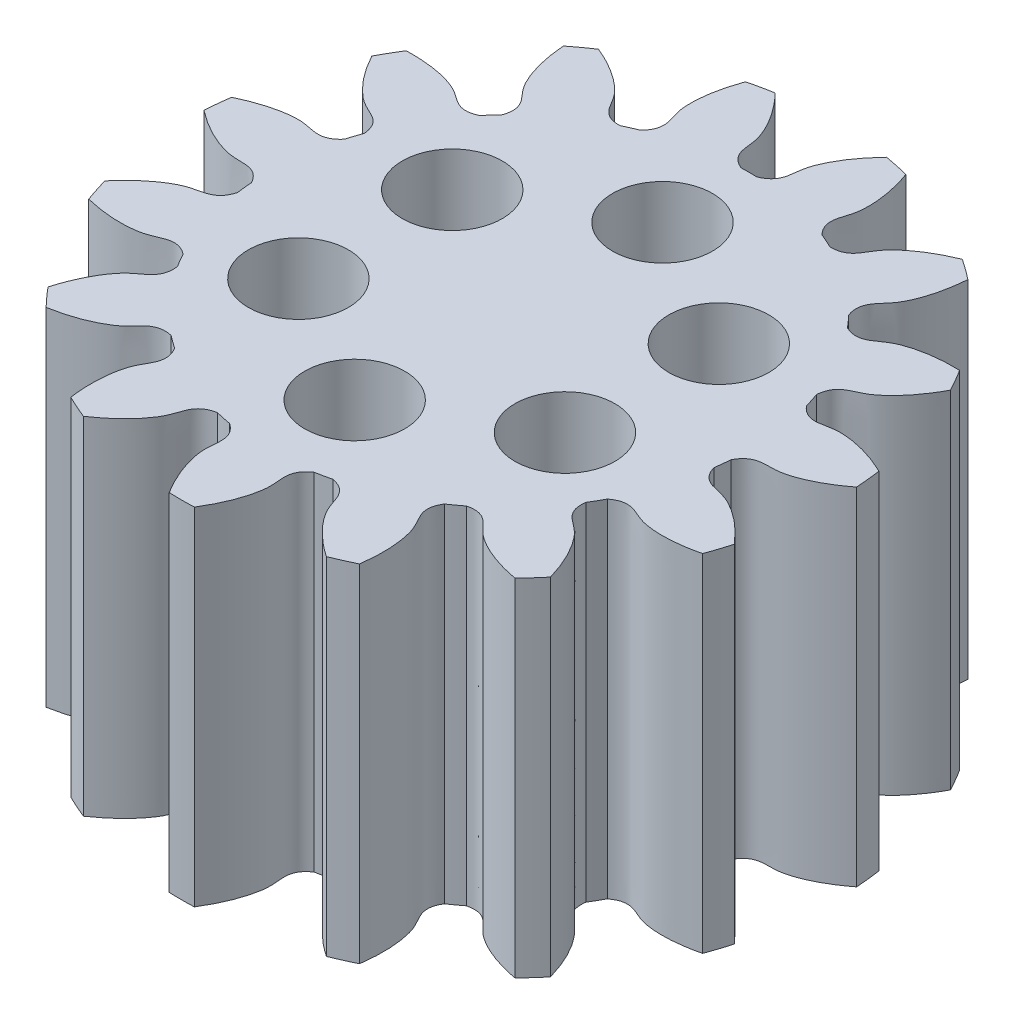
SolidWorks part; units mm, degrees
ref_plane "前视基准面" through (0, 0, 0) normal (0, 0, 1) x (1, 0, 0)
ref_plane "上视基准面" through (0, 0, 0) normal (0, 1, 0) x (1, 0, 0)
ref_plane "右视基准面" through (0, 0, 0) normal (1, 0, 0) x (0, 0, -1)
other "Configuration Table"
sketch "草图1" plane through (0, 0, 0) normal (0, 1, 0) x (1, 0, 0)
  arc A0 (-4.0703, 11.2781) -> (-4.8168, 10.9457) centre (0.638, -0.3013) ccw
  arc A1 (-8.8187, 13.8256) -> (-9.8753, 13.058) centre (0.638, -0.3013) ccw
  arc A2 (-8.373, 8.362) -> (-8.9198, 7.7547) centre (0.638, -0.3013) ccw
  arc A3 (-13.7471, 8.7579) -> (-14.4001, 7.6269) centre (0.638, -0.3013) ccw
  arc A4 (-11.1176, 3.9479) -> (-11.3701, 3.1708) centre (0.638, -0.3013) ccw
  arc A5 (-16.1882, 2.1238) -> (-16.3247, 0.8249) centre (0.638, -0.3013) ccw
  arc A6 (-11.8296, -1.2009) -> (-11.7442, -2.0136) centre (0.638, -0.3013) ccw
  arc A7 (-15.7198, -4.9297) -> (-15.3163, -6.1718) centre (0.638, -0.3013) ccw
  arc A8 (-10.3858, -6.1942) -> (-9.9773, -6.9018) centre (0.638, -0.3013) ccw
  arc A9 (-12.4231, -11.1829) -> (-11.5492, -12.1534) centre (0.638, -0.3013) ccw
  arc A10 (-7.0359, -10.1685) -> (-6.3749, -10.6488) centre (0.638, -0.3013) ccw
  arc A11 (-6.868, -15.5545) -> (-5.6749, -16.0857) centre (0.638, -0.3013) ccw
  arc A12 (-2.3592, -12.4367) -> (-1.5599, -12.6066) centre (0.638, -0.3013) ccw
  arc A13 (-0.015, -17.2888) -> (1.291, -17.2888) centre (0.638, -0.3013) ccw
  arc A14 (2.8358, -12.6066) -> (3.6351, -12.4367) centre (0.638, -0.3013) ccw
  arc A15 (6.9509, -16.0857) -> (8.1439, -15.5545) centre (0.638, -0.3013) ccw
  arc A16 (7.6508, -10.6488) -> (8.3119, -10.1685) centre (0.638, -0.3013) ccw
  arc A17 (12.8252, -12.1534) -> (13.6991, -11.1829) centre (0.638, -0.3013) ccw
  arc A18 (11.2532, -6.9018) -> (11.6618, -6.1942) centre (0.638, -0.3013) ccw
  arc A19 (16.5922, -6.1718) -> (16.9958, -4.9297) centre (0.638, -0.3013) ccw
  arc A20 (13.0202, -2.0136) -> (13.1056, -1.2009) centre (0.638, -0.3013) ccw
  arc A21 (17.6006, 0.8249) -> (17.4641, 2.1238) centre (0.638, -0.3013) ccw
  arc A22 (12.6461, 3.1708) -> (12.3936, 3.9479) centre (0.638, -0.3013) ccw
  arc A23 (15.676, 7.6269) -> (15.0231, 8.7579) centre (0.638, -0.3013) ccw
  arc A24 (10.1957, 7.7547) -> (9.6489, 8.362) centre (0.638, -0.3013) ccw
  arc A25 (11.1512, 13.058) -> (10.0947, 13.8256) centre (0.638, -0.3013) ccw
  arc A26 (6.0927, 10.9457) -> (5.3462, 11.2781) centre (0.638, -0.3013) ccw
  arc A27 (4.8086, 16.1792) -> (3.5312, 16.4507) centre (0.638, -0.3013) ccw
  arc A28 (1.0466, 12.192) -> (0.2294, 12.192) centre (0.638, -0.3013) ccw
  arc A29 (-2.2552, 16.4507) -> (-3.5326, 16.1792) centre (0.638, -0.3013) ccw
  spline S0 degree 3 poles (-4.8168, 10.9457) (-5.797, 10.9203) (-5.9278, 11.6325) (-6.3455, 12.1709) (-6.3886, 12.223) (-6.4381, 12.2796) (-6.4989, 12.3462) (-6.5873, 12.4373) (-6.7098, 12.5539) (-6.8539, 12.6805) (-7.0204, 12.8153) (-7.2102, 12.957) (-7.4242, 13.1037) (-7.6629, 13.2537) (-7.927, 13.4053) (-8.2169, 13.5567) (-8.5165, 13.6982) (-8.7208, 13.7857) (-8.8187, 13.8256) knots 0.470856 0.470856 0.470856 0.470856 0.673329 0.677835 0.688649 0.694957 0.701866 0.717486 0.735509 0.755935 0.778765 0.803997 0.831633 0.861672 0.894113 0.928958 0.966206 1 1 1 1
  spline S1 degree 3 poles (-9.8753, 13.058) (-9.8632, 12.8935) (-9.8356, 12.6171) (-9.7794, 12.2383) (-9.7207, 11.928) (-9.6547, 11.6422) (-9.5833, 11.3811) (-9.5084, 11.1446) (-9.4317, 10.9325) (-9.3661, 10.7714) (-9.3033, 10.6297) (-9.2546, 10.5279) (-9.2062, 10.4345) (-9.1726, 10.3725) (-9.1405, 10.3162) (-9.1021, 10.2516) (-9.0658, 10.1944) (-8.6828, 9.6309) (-8.0459, 9.2864) (-8.373, 8.362) knots 0 0 0 0 0.052718 0.088765 0.122408 0.153648 0.182485 0.208919 0.23295 0.254578 0.264491 0.282514 0.290624 0.298134 0.305043 0.311351 0.322165 0.326671 0.529144 0.529144 0.529144 0.529144
  spline S2 degree 3 poles (-8.9198, 7.7547) (-9.8049, 7.3328) (-10.2141, 7.9302) (-10.8146, 8.2522) (-10.8752, 8.2823) (-10.9435, 8.3138) (-11.0261, 8.35) (-11.1439, 8.3972) (-11.3033, 8.4539) (-11.4863, 8.5109) (-11.6933, 8.5664) (-11.9244, 8.6186) (-12.1795, 8.6656) (-12.4586, 8.7055) (-12.7615, 8.7366) (-13.088, 8.757) (-13.4192, 8.7644) (-13.6414, 8.7612) (-13.7471, 8.7579) knots 0.470856 0.470856 0.470856 0.470856 0.673329 0.677835 0.688649 0.694957 0.701866 0.717486 0.735509 0.755935 0.778765 0.803997 0.831633 0.861672 0.894113 0.928958 0.966206 1 1 1 1
  spline S3 degree 3 poles (-14.4001, 7.6269) (-14.3221, 7.4816) (-14.1845, 7.2403) (-13.9791, 6.917) (-13.7993, 6.6574) (-13.6228, 6.4232) (-13.4513, 6.2138) (-13.2867, 6.0282) (-13.1303, 5.8655) (-13.0049, 5.7451) (-12.8899, 5.6412) (-12.804, 5.568) (-12.7218, 5.5023) (-12.6659, 5.4594) (-12.6137, 5.4209) (-12.5522, 5.3776) (-12.4959, 5.3402) (-11.9168, 4.9811) (-11.1948, 4.9255) (-11.1176, 3.9479) knots 0 0 0 0 0.052718 0.088765 0.122408 0.153648 0.182485 0.208919 0.23295 0.254578 0.264491 0.282514 0.290624 0.298134 0.305043 0.311351 0.322165 0.326671 0.529144 0.529144 0.529144 0.529144
  spline S4 degree 3 poles (-11.3701, 3.1708) (-12.0072, 2.4253) (-12.624, 2.8046) (-13.3035, 2.8545) (-13.3711, 2.8574) (-13.4463, 2.8584) (-13.5365, 2.8578) (-13.6633, 2.8531) (-13.832, 2.84) (-14.0224, 2.8176) (-14.2341, 2.7842) (-14.4663, 2.7379) (-14.7185, 2.677) (-14.9897, 2.6) (-15.2791, 2.5052) (-15.5856, 2.391) (-15.8913, 2.2631) (-16.093, 2.1697) (-16.1882, 2.1238) knots 0.470856 0.470856 0.470856 0.470856 0.673329 0.677835 0.688649 0.694957 0.701866 0.717486 0.735509 0.755935 0.778765 0.803997 0.831633 0.861672 0.894113 0.928958 0.966206 1 1 1 1
  spline S5 degree 3 poles (-16.3247, 0.8249) (-16.1943, 0.7239) (-15.9705, 0.5594) (-15.6514, 0.3476) (-15.3815, 0.1837) (-15.125, 0.0415) (-14.8832, -0.0801) (-14.6572, -0.1827) (-14.4483, -0.2677) (-14.2847, -0.3267) (-14.1373, -0.3749) (-14.0292, -0.4067) (-13.9273, -0.4334) (-13.8588, -0.4498) (-13.7955, -0.4637) (-13.7217, -0.4783) (-13.655, -0.4896) (-12.9799, -0.5821) (-12.2977, -0.3393) (-11.8296, -1.2009) knots 0 0 0 0 0.052718 0.088765 0.122408 0.153648 0.182485 0.208919 0.23295 0.254578 0.264491 0.282514 0.290624 0.298134 0.305043 0.311351 0.322165 0.326671 0.529144 0.529144 0.529144 0.529144
  spline S6 degree 3 poles (-11.7442, -2.0136) (-12.0229, -2.9537) (-12.7407, -2.858) (-13.3818, -3.0888) (-13.4447, -3.1137) (-13.5138, -3.1434) (-13.596, -3.1806) (-13.7099, -3.2365) (-13.8587, -3.317) (-14.0235, -3.4149) (-14.2033, -3.5316) (-14.3966, -3.6684) (-14.6023, -3.8265) (-14.8187, -4.0072) (-15.0445, -4.2115) (-15.2781, -4.4405) (-15.5053, -4.6817) (-15.6516, -4.849) (-15.7198, -4.9297) knots 0.470856 0.470856 0.470856 0.470856 0.673329 0.677835 0.688649 0.694957 0.701866 0.717486 0.735509 0.755935 0.778765 0.803997 0.831633 0.861672 0.894113 0.928958 0.966206 1 1 1 1
  spline S7 degree 3 poles (-15.3163, -6.1718) (-15.1561, -6.2111) (-14.8847, -6.2702) (-14.507, -6.3339) (-14.1938, -6.374) (-13.9016, -6.3995) (-13.6313, -6.4123) (-13.3831, -6.4141) (-13.1577, -6.4067) (-12.9843, -6.3942) (-12.83, -6.3782) (-12.7182, -6.3633) (-12.6144, -6.3462) (-12.5451, -6.3333) (-12.4816, -6.3203) (-12.4083, -6.3036) (-12.3427, -6.2868) (-11.6884, -6.0967) (-11.164, -5.5974) (-10.3858, -6.1942) knots 0 0 0 0 0.052718 0.088765 0.122408 0.153648 0.182485 0.208919 0.23295 0.254578 0.264491 0.282514 0.290624 0.298134 0.305043 0.311351 0.322165 0.326671 0.529144 0.529144 0.529144 0.529144
  spline S8 degree 3 poles (-9.9773, -6.9018) (-9.8495, -7.8741) (-10.5442, -8.0786) (-11.0359, -8.5502) (-11.0833, -8.5985) (-11.1344, -8.6537) (-11.1943, -8.7211) (-11.2756, -8.8185) (-11.3788, -8.9526) (-11.4896, -9.1091) (-11.6063, -9.2888) (-11.7273, -9.4924) (-11.8509, -9.7205) (-11.9751, -9.9736) (-12.0983, -10.2521) (-12.2186, -10.5563) (-12.328, -10.869) (-12.3936, -11.0814) (-12.4231, -11.1829) knots 0.470856 0.470856 0.470856 0.470856 0.673329 0.677835 0.688649 0.694957 0.701866 0.717486 0.735509 0.755935 0.778765 0.803997 0.831633 0.861672 0.894113 0.928958 0.966206 1 1 1 1
  spline S9 degree 3 poles (-11.5492, -12.1534) (-11.3869, -12.1242) (-11.1149, -12.0678) (-10.744, -11.9724) (-10.4415, -11.8816) (-10.1643, -11.7861) (-9.9121, -11.6878) (-9.6847, -11.5885) (-9.4817, -11.4901) (-9.3284, -11.4081) (-9.194, -11.3307) (-9.0979, -11.2717) (-9.01, -11.2138) (-8.9519, -11.1739) (-8.8992, -11.1361) (-8.839, -11.0911) (-8.786, -11.049) (-8.2655, -10.6093) (-7.9895, -9.9398) (-7.0359, -10.1685) knots 0 0 0 0 0.052718 0.088765 0.122408 0.153648 0.182485 0.208919 0.23295 0.254578 0.264491 0.282514 0.290624 0.298134 0.305043 0.311351 0.322165 0.326671 0.529144 0.529144 0.529144 0.529144
  spline S10 degree 3 poles (-6.3749, -10.6488) (-5.8627, -11.485) (-6.4141, -11.9544) (-6.6715, -12.5853) (-6.6951, -12.6487) (-6.7194, -12.7199) (-6.7467, -12.8058) (-6.7814, -12.9279) (-6.8211, -13.0923) (-6.8586, -13.2804) (-6.8922, -13.492) (-6.9199, -13.7272) (-6.94, -13.9859) (-6.9506, -14.2676) (-6.9498, -14.5721) (-6.936, -14.8989) (-6.9087, -15.2291) (-6.8823, -15.4498) (-6.868, -15.5545) knots 0.470856 0.470856 0.470856 0.470856 0.673329 0.677835 0.688649 0.694957 0.701866 0.717486 0.735509 0.755935 0.778765 0.803997 0.831633 0.861672 0.894113 0.928958 0.966206 1 1 1 1
  spline S11 degree 3 poles (-5.6749, -16.0857) (-5.5385, -15.993) (-5.3129, -15.8309) (-5.0129, -15.5929) (-4.7735, -15.3869) (-4.5591, -15.1868) (-4.3687, -14.9945) (-4.2013, -14.8113) (-4.0559, -14.6388) (-3.9492, -14.5015) (-3.8579, -14.3762) (-3.7942, -14.2832) (-3.7374, -14.1946) (-3.7005, -14.1345) (-3.6678, -14.0785) (-3.6311, -14.0129) (-3.5997, -13.9529) (-3.3032, -13.3395) (-3.3233, -12.6156) (-2.3592, -12.4367) knots 0 0 0 0 0.052718 0.088765 0.122408 0.153648 0.182485 0.208919 0.23295 0.254578 0.264491 0.282514 0.290624 0.298134 0.305043 0.311351 0.322165 0.326671 0.529144 0.529144 0.529144 0.529144
  spline S12 degree 3 poles (-1.5599, -12.6066) (-0.7519, -13.1622) (-1.0647, -13.8153) (-1.0433, -14.4963) (-1.039, -14.5638) (-1.0322, -14.6387) (-1.0222, -14.7284) (-1.0042, -14.854) (-0.9736, -15.0204) (-0.9315, -15.2074) (-0.876, -15.4144) (-0.8057, -15.6406) (-0.7189, -15.885) (-0.6139, -16.1467) (-0.4894, -16.4246) (-0.3438, -16.7175) (-0.1846, -17.0081) (-0.0707, -17.1989) (-0.015, -17.2888) knots 0.470856 0.470856 0.470856 0.470856 0.673329 0.677835 0.688649 0.694957 0.701866 0.717486 0.735509 0.755935 0.778765 0.803997 0.831633 0.861672 0.894113 0.928958 0.966206 1 1 1 1
  spline S13 degree 3 poles (1.291, -17.2888) (1.3778, -17.1486) (1.518, -16.9088) (1.6953, -16.5693) (1.8301, -16.2837) (1.9447, -16.0138) (2.0404, -15.7606) (2.1188, -15.5252) (2.1815, -15.3085) (2.2231, -15.1396) (2.2556, -14.988) (2.276, -14.8771) (2.2918, -14.773) (2.301, -14.7032) (2.3082, -14.6387) (2.315, -14.5638) (2.3192, -14.4963) (2.3407, -13.8153) (2.0279, -13.1622) (2.8358, -12.6066) knots 0 0 0 0 0.052718 0.088765 0.122408 0.153648 0.182485 0.208919 0.23295 0.254578 0.264491 0.282514 0.290624 0.298134 0.305043 0.311351 0.322165 0.326671 0.529144 0.529144 0.529144 0.529144
  spline S14 degree 3 poles (3.6351, -12.4367) (4.5993, -12.6156) (4.5791, -13.3395) (4.8757, -13.9529) (4.907, -14.0129) (4.9437, -14.0785) (4.9893, -14.1564) (5.0568, -14.2638) (5.1525, -14.4033) (5.2671, -14.5571) (5.4019, -14.7236) (5.5581, -14.9016) (5.7369, -15.0896) (5.9392, -15.286) (6.166, -15.4892) (6.4181, -15.6976) (6.6818, -15.8983) (6.8635, -16.0263) (6.9509, -16.0857) knots 0.470856 0.470856 0.470856 0.470856 0.673329 0.677835 0.688649 0.694957 0.701866 0.717486 0.735509 0.755935 0.778765 0.803997 0.831633 0.861672 0.894113 0.928958 0.966206 1 1 1 1
  spline S15 degree 3 poles (8.1439, -15.5545) (8.1663, -15.3911) (8.1968, -15.115) (8.2206, -14.7328) (8.2277, -14.4171) (8.2226, -14.1239) (8.207, -13.8536) (8.1829, -13.6067) (8.152, -13.3832) (8.1213, -13.2121) (8.0893, -13.0604) (8.0628, -12.9507) (8.035, -12.8492) (8.015, -12.7816) (7.9953, -12.7199) (7.9711, -12.6487) (7.9475, -12.5853) (7.6901, -11.9544) (7.1387, -11.485) (7.6508, -10.6488) knots 0 0 0 0 0.052718 0.088765 0.122408 0.153648 0.182485 0.208919 0.23295 0.254578 0.264491 0.282514 0.290624 0.298134 0.305043 0.311351 0.322165 0.326671 0.529144 0.529144 0.529144 0.529144
  spline S16 degree 3 poles (8.3119, -10.1685) (9.2655, -9.9398) (9.5415, -10.6093) (10.0619, -11.049) (10.115, -11.0911) (10.1752, -11.1361) (10.2485, -11.1887) (10.3539, -11.2594) (10.498, -11.348) (10.6652, -11.4418) (10.8561, -11.5391) (11.0712, -11.6382) (11.311, -11.7372) (11.5757, -11.8343) (11.8656, -11.9277) (12.1806, -12.0155) (12.5031, -12.0916) (12.7212, -12.1347) (12.8252, -12.1534) knots 0.470856 0.470856 0.470856 0.470856 0.673329 0.677835 0.688649 0.694957 0.701866 0.717486 0.735509 0.755935 0.778765 0.803997 0.831633 0.861672 0.894113 0.928958 0.966206 1 1 1 1
  spline S17 degree 3 poles (13.6991, -11.1829) (13.653, -11.0245) (13.5686, -10.7599) (13.4349, -10.401) (13.3129, -10.1097) (13.189, -9.8439) (13.0648, -9.6034) (12.9424, -9.3876) (12.8233, -9.196) (12.7257, -9.0521) (12.6347, -8.9265) (12.5659, -8.8372) (12.4992, -8.7558) (12.4534, -8.7022) (12.4103, -8.6537) (12.3593, -8.5985) (12.3119, -8.5502) (11.8201, -8.0786) (11.1255, -7.8741) (11.2532, -6.9018) knots 0 0 0 0 0.052718 0.088765 0.122408 0.153648 0.182485 0.208919 0.23295 0.254578 0.264491 0.282514 0.290624 0.298134 0.305043 0.311351 0.322165 0.326671 0.529144 0.529144 0.529144 0.529144
  spline S18 degree 3 poles (11.6618, -6.1942) (12.4399, -5.5974) (12.9644, -6.0967) (13.6187, -6.2868) (13.6842, -6.3036) (13.7575, -6.3203) (13.8459, -6.3385) (13.9709, -6.3602) (14.1386, -6.3825) (14.3295, -6.4002) (14.5435, -6.4115) (14.7804, -6.4144) (15.0397, -6.4074) (15.321, -6.3884) (15.6238, -6.3559) (15.9473, -6.3079) (16.2728, -6.2463) (16.4896, -6.197) (16.5922, -6.1718) knots 0.470856 0.470856 0.470856 0.470856 0.673329 0.677835 0.688649 0.694957 0.701866 0.717486 0.735509 0.755935 0.778765 0.803997 0.831633 0.861672 0.894113 0.928958 0.966206 1 1 1 1
  spline S19 degree 3 poles (16.9958, -4.9297) (16.8893, -4.8038) (16.7045, -4.5964) (16.4364, -4.3229) (16.2065, -4.1063) (15.9852, -3.914) (15.774, -3.7447) (15.5743, -3.5974) (15.3876, -3.4708) (15.2399, -3.3791) (15.1057, -3.3014) (15.0065, -3.2477) (14.9125, -3.2005) (14.8488, -3.1701) (14.7898, -3.1434) (14.7207, -3.1137) (14.6578, -3.0888) (14.0167, -2.858) (13.2989, -2.9537) (13.0202, -2.0136) knots 0 0 0 0 0.052718 0.088765 0.122408 0.153648 0.182485 0.208919 0.23295 0.254578 0.264491 0.282514 0.290624 0.298134 0.305043 0.311351 0.322165 0.326671 0.529144 0.529144 0.529144 0.529144
  spline S20 degree 3 poles (13.1056, -1.2009) (13.5737, -0.3393) (14.2559, -0.5821) (14.9309, -0.4896) (14.9977, -0.4783) (15.0714, -0.4637) (15.1595, -0.4444) (15.2826, -0.4134) (15.4449, -0.3656) (15.6265, -0.3041) (15.8265, -0.2273) (16.0441, -0.1337) (16.2781, -0.0218) (16.5274, 0.1099) (16.7908, 0.2628) (17.0669, 0.4382) (17.3392, 0.6269) (17.5171, 0.7602) (17.6006, 0.8249) knots 0.470856 0.470856 0.470856 0.470856 0.673329 0.677835 0.688649 0.694957 0.701866 0.717486 0.735509 0.755935 0.778765 0.803997 0.831633 0.861672 0.894113 0.928958 0.966206 1 1 1 1
  spline S21 degree 3 poles (17.4641, 2.1238) (17.3156, 2.1955) (17.0625, 2.3098) (16.7063, 2.4506) (16.4082, 2.5549) (16.1278, 2.6406) (15.8659, 2.7094) (15.6236, 2.7627) (15.4016, 2.8024) (15.2293, 2.8261) (15.0751, 2.8426) (14.9627, 2.8513) (14.8575, 2.8561) (14.7871, 2.858) (14.7223, 2.8584) (14.6471, 2.8574) (14.5795, 2.8545) (13.8999, 2.8046) (13.2831, 2.4253) (12.6461, 3.1708) knots 0 0 0 0 0.052718 0.088765 0.122408 0.153648 0.182485 0.208919 0.23295 0.254578 0.264491 0.282514 0.290624 0.298134 0.305043 0.311351 0.322165 0.326671 0.529144 0.529144 0.529144 0.529144
  spline S22 degree 3 poles (12.3936, 3.9479) (12.4708, 4.9255) (13.1928, 4.9811) (13.7718, 5.3402) (13.8282, 5.3776) (13.8896, 5.4209) (13.9623, 5.4744) (14.0621, 5.5528) (14.1909, 5.6625) (14.3318, 5.7925) (14.4833, 5.944) (14.644, 6.118) (14.8123, 6.3155) (14.9864, 6.5372) (15.1648, 6.784) (15.3457, 7.0565) (15.5177, 7.3397) (15.6261, 7.5338) (15.676, 7.6269) knots 0.470856 0.470856 0.470856 0.470856 0.673329 0.677835 0.688649 0.694957 0.701866 0.717486 0.735509 0.755935 0.778765 0.803997 0.831633 0.861672 0.894113 0.928958 0.966206 1 1 1 1
  spline S23 degree 3 poles (15.0231, 8.7579) (14.8582, 8.763) (14.5804, 8.7645) (14.1978, 8.7483) (13.8831, 8.7223) (13.592, 8.6866) (13.3249, 8.6428) (13.0818, 8.593) (12.8628, 8.539) (12.6958, 8.4906) (12.5482, 8.4429) (12.442, 8.4051) (12.344, 8.3668) (12.2788, 8.3398) (12.2194, 8.3138) (12.1512, 8.2823) (12.0906, 8.2522) (11.4901, 7.9302) (11.0809, 7.3328) (10.1957, 7.7547) knots 0 0 0 0 0.052718 0.088765 0.122408 0.153648 0.182485 0.208919 0.23295 0.254578 0.264491 0.282514 0.290624 0.298134 0.305043 0.311351 0.322165 0.326671 0.529144 0.529144 0.529144 0.529144
  spline S24 degree 3 poles (9.6489, 8.362) (9.3219, 9.2864) (9.9588, 9.6309) (10.3418, 10.1944) (10.378, 10.2516) (10.4165, 10.3162) (10.4611, 10.3946) (10.5204, 10.5067) (10.5935, 10.6593) (10.6693, 10.8355) (10.7461, 11.0355) (10.8221, 11.2598) (10.8955, 11.5086) (10.9645, 11.782) (11.0271, 12.08) (11.0814, 12.4026) (11.1234, 12.7312) (11.1435, 12.9526) (11.1512, 13.058) knots 0.470856 0.470856 0.470856 0.470856 0.673329 0.677835 0.688649 0.694957 0.701866 0.717486 0.735509 0.755935 0.778765 0.803997 0.831633 0.861672 0.894113 0.928958 0.966206 1 1 1 1
  spline S25 degree 3 poles (10.0947, 13.8256) (9.942, 13.7633) (9.6877, 13.6516) (9.3447, 13.4812) (9.0677, 13.3294) (8.8164, 13.1784) (8.5901, 13.0298) (8.3883, 12.8854) (8.2102, 12.747) (8.0773, 12.6348) (7.962, 12.5312) (7.8803, 12.4535) (7.8063, 12.3786) (7.7578, 12.3275) (7.7141, 12.2796) (7.6645, 12.223) (7.6214, 12.1709) (7.2038, 11.6325) (7.073, 10.9203) (6.0927, 10.9457) knots 0 0 0 0 0.052718 0.088765 0.122408 0.153648 0.182485 0.208919 0.23295 0.254578 0.264491 0.282514 0.290624 0.298134 0.305043 0.311351 0.322165 0.326671 0.529144 0.529144 0.529144 0.529144
  spline S26 degree 3 poles (5.3462, 11.2781) (4.6714, 11.9896) (5.1132, 12.5633) (5.2338, 13.2339) (5.2437, 13.3009) (5.2526, 13.3755) (5.2615, 13.4653) (5.27, 13.5919) (5.2746, 13.761) (5.2723, 13.9527) (5.2611, 14.1667) (5.2393, 14.4026) (5.2052, 14.6597) (5.157, 14.9375) (5.0929, 15.2352) (5.0114, 15.552) (4.9161, 15.8693) (4.8444, 16.0797) (4.8086, 16.1792) knots 0.470856 0.470856 0.470856 0.470856 0.673329 0.677835 0.688649 0.694957 0.701866 0.717486 0.735509 0.755935 0.778765 0.803997 0.831633 0.861672 0.894113 0.928958 0.966206 1 1 1 1
  spline S27 degree 3 poles (3.5312, 16.4507) (3.417, 16.3316) (3.2301, 16.1262) (2.9861, 15.8309) (2.7948, 15.5797) (2.6266, 15.3394) (2.4804, 15.1117) (2.3547, 14.8977) (2.2484, 14.6988) (2.1726, 14.5423) (2.1093, 14.4007) (2.0663, 14.2965) (2.0292, 14.198) (2.0056, 14.1316) (1.9852, 14.07) (1.963, 13.9982) (1.9448, 13.933) (1.7822, 13.2713) (1.9524, 12.5675) (1.0466, 12.192) knots 0 0 0 0 0.052718 0.088765 0.122408 0.153648 0.182485 0.208919 0.23295 0.254578 0.264491 0.282514 0.290624 0.298134 0.305043 0.311351 0.322165 0.326671 0.529144 0.529144 0.529144 0.529144
  spline S28 degree 3 poles (0.2294, 12.192) (-0.6764, 12.5675) (-0.5062, 13.2713) (-0.6688, 13.933) (-0.687, 13.9982) (-0.7092, 14.07) (-0.7377, 14.1556) (-0.7813, 14.2748) (-0.8459, 14.4312) (-0.926, 14.6053) (-1.0233, 14.7963) (-1.1391, 15.0029) (-1.2749, 15.2239) (-1.4319, 15.4581) (-1.6115, 15.704) (-1.8148, 15.9602) (-2.0309, 16.2114) (-2.182, 16.3744) (-2.2552, 16.4507) knots 0.470856 0.470856 0.470856 0.470856 0.673329 0.677835 0.688649 0.694957 0.701866 0.717486 0.735509 0.755935 0.778765 0.803997 0.831633 0.861672 0.894113 0.928958 0.966206 1 1 1 1
  spline S29 degree 3 poles (-3.5326, 16.1792) (-3.5884, 16.024) (-3.6757, 15.7602) (-3.7785, 15.3913) (-3.8511, 15.0839) (-3.907, 14.7961) (-3.948, 14.5285) (-3.9757, 14.2819) (-3.992, 14.057) (-3.9976, 13.8832) (-3.9978, 13.7281) (-3.9947, 13.6154) (-3.9885, 13.5103) (-3.983, 13.44) (-3.9766, 13.3755) (-3.9677, 13.3009) (-3.9578, 13.2339) (-3.8372, 12.5633) (-3.3954, 11.9896) (-4.0703, 11.2781) knots 0 0 0 0 0.052718 0.088765 0.122408 0.153648 0.182485 0.208919 0.23295 0.254578 0.264491 0.282514 0.290624 0.298134 0.305043 0.311351 0.322165 0.326671 0.529144 0.529144 0.529144 0.529144
extrude "凸台-拉伸1" add sketch "草图1" along normal blind 18
sketch "草图2" plane through (0, 18, 0) normal (0, 1, 0) x (1, 0, 0)
  circle A1 centre (0.638, 7.6987) radius 2.6
  circle A7 centre (7.5662, 3.6987) radius 2.6
  circle A8 centre (7.5662, -4.3013) radius 2.6
  circle A9 centre (0.638, -8.3013) radius 2.6
  arc A10 (12.6461, 3.1708) -> (12.3936, 3.9479) centre (0.638, -0.3013) ccw construction
  arc A11 (12.6461, 3.1708) -> (12.3936, 3.9479) centre (0.638, -0.3013) ccw
  circle A12 centre (0.638, -0.3013) radius 12.5
  circle A13 centre (0.638, -0.3013) radius 8 construction
  circle A14 centre (-6.2902, -4.3013) radius 2.6
  circle A15 centre (-6.2902, 3.6987) radius 2.6
  point P14 (0.638, -0.3013)
  point P17 (0, 0)
  dimension "D1" = 6
  dimension "D2" = 5.2
  dimension "D4" = 16
extrude "切除-拉伸1" cut sketch "草图2" against normal blind 18
move or copy body "实体-移动/复制1" [suppressed] bodies to move or copy 116 parameters "D1"=0, "D2"=0, "D3"=0
move or copy body "实体-移动/复制2" [suppressed] bodies to move or copy 117 parameters "D1"=0, "D2"=0, "D3"=0
